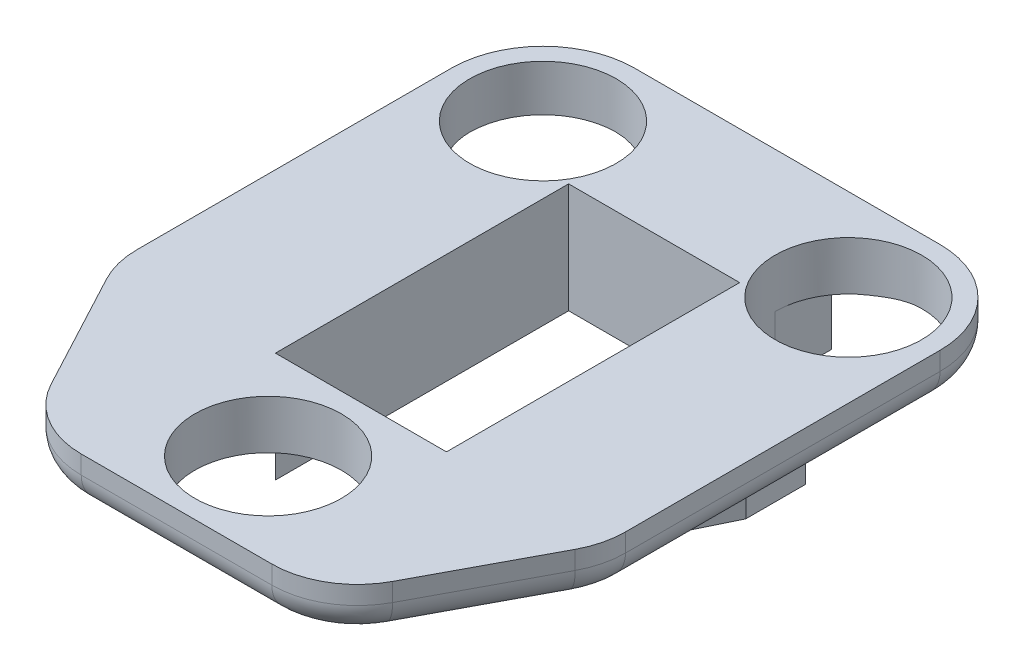
SolidWorks part; units mm, degrees
ref_plane "Front" through (0, 0, 0) normal (0, 0, 1) x (1, 0, 0)
ref_plane "Top" through (0, 0, 0) normal (0, 1, 0) x (1, 0, 0)
ref_plane "Right" through (0, 0, 0) normal (1, 0, 0) x (0, 0, -1)
sketch "Sketch2" plane through (0, 202.9635, 0) normal (0, -1, 0) x (1, 0, 0)
  line L6 (-139.7647, 258.9047) -> (-191.7647, 161.4047)
  line L7 (-200, 128.4635) -> (-200, -129.0365)
  line L8 (-125, -204.0365) -> (125, -204.0365)
  line L9 (200, -129.0365) -> (200, 128.4635)
  line L10 (191.7647, 161.4047) -> (139.7647, 258.9047)
  line L11 (78, 295.9635) -> (-78, 295.9635)
  line L12 (-139.7647, 258.9047) -> (-191.7647, 161.4047)
  line L13 (-200, 128.4635) -> (-200, -129.0365)
  line L14 (-125, -204.0365) -> (125, -204.0365)
  line L15 (200, -129.0365) -> (200, 128.4635)
  line L16 (191.7647, 161.4047) -> (139.7647, 258.9047)
  line L17 (78, 295.9635) -> (-78, 295.9635)
  arc A6 (-191.7647, 161.4047) -> (-200, 128.4635) centre (-130, 128.4635) ccw
  arc A7 (-200, -129.0365) -> (-125, -204.0365) centre (-125, -129.0365) ccw
  arc A8 (125, -204.0365) -> (200, -129.0365) centre (125, -129.0365) ccw
  arc A9 (200, 128.4635) -> (191.7647, 161.4047) centre (130, 128.4635) ccw
  arc A10 (139.7647, 258.9047) -> (78, 295.9635) centre (78, 225.9635) ccw
  arc A11 (-78, 295.9635) -> (-139.7647, 258.9047) centre (-78, 225.9635) ccw
  arc A12 (-191.7647, 161.4047) -> (-200, 128.4635) centre (-130, 128.4635) ccw
  arc A13 (-200, -129.0365) -> (-125, -204.0365) centre (-125, -129.0365) ccw
  arc A14 (125, -204.0365) -> (200, -129.0365) centre (125, -129.0365) ccw
  arc A15 (200, 128.4635) -> (191.7647, 161.4047) centre (130, 128.4635) ccw
  arc A16 (139.7647, 258.9047) -> (78, 295.9635) centre (78, 225.9635) ccw
  arc A17 (-78, 295.9635) -> (-139.7647, 258.9047) centre (-78, 225.9635) ccw
  dimension "D1" = 0
extrude "Boss-Extrude1" add sketch "Sketch2" along normal blind 40
fillet "Fillet1" radius 25 12 edges at (178.033, 162.9635, -182.0695) (0, 162.9635, -204.0365) (-178.033, 162.9635, -182.0695) (-200, 162.9635, -0.2865) (-197.91, 162.9635, 145.441) (-165.7647, 162.9635, 210.1547) (-114.0147, 162.9635, 285.988) (0, 162.9635, 295.9635) (114.0147, 162.9635, 285.988) (165.7647, 162.9635, 210.1547) (197.91, 162.9635, 145.441) (200, 162.9635, -0.2865)
sketch "Sketch3" plane through (0, 162.9635, 0) normal (0, -1, 0) x (1, 0, 0)
  line L0 (0, 145) -> (0, 0) construction
  line L1 (-70, 145) -> (70, 145)
  line L2 (-70, 145) -> (-70, -95)
  line L3 (-70, -95) -> (70, -95)
  line L4 (70, 145) -> (70, -95)
  line L5 (-125, -129) -> (125, -129) construction
  line L6 (0, 221) -> (0, -129) construction
  circle A3 centre (0, 221) radius 60
  circle A4 centre (125, -129) radius 60
  circle A5 centre (-125, -129) radius 60
  dimension "D7" = 120
  dimension "D1" = 145
  dimension "D2" = 70
  dimension "D3" = 240
  dimension "D4" = 129
  dimension "D5" = 250
  dimension "D6" = 350
extrude "Cut-Extrude1" cut sketch "Sketch3" against normal through all
sketch "Sketch4" plane through (0, 162.9635, 0) normal (0, -1, 0) x (1, 0, 0)
  line L0 (70, -95) -> (70, 145) construction
  line L2 (-150, -20) -> (-150, -69)
  line L3 (-150, -69) -> (-70, -69)
  line L4 (-70, 145) -> (-70, -69)
  line L6 (150, -20) -> (150, -69)
  line L7 (150, -69) -> (70, -69)
  line L8 (70, 145) -> (70, -69)
  line L9 (-70, 145) -> (-70, -95) construction
  line L11 (-70, -95) -> (70, -95) construction
  line L12 (-65, -95) -> (65, -95)
  line L13 (-65, -95) -> (-65, -175)
  line L14 (-65, -175) -> (65, -175)
  line L15 (65, -95) -> (65, -175)
  line L16 (0, -95) -> (0, 0) construction
  line L17 (70, -69) -> (70, -95)
  line L18 (70, -95) -> (65, -95)
  line L19 (-70, -69) -> (-70, -95)
  line L20 (-70, -95) -> (-65, -95)
  line L21 (-70, 145) -> (-150, -20)
  line L22 (70, 145) -> (150, -20)
  line L23 (-150, -20) -> (150, -20) construction
  arc A0 (-91.8889, -179.0365) -> (-175, -95.8338) centre (-125, -129) ccw construction
  arc A1 (-65, -129) -> (-125, -69) centre (-125, -129) ccw
  arc A2 (175, -95.8338) -> (91.8889, -179.0365) centre (125, -129) ccw construction
  arc A3 (125, -69) -> (65, -129) centre (125, -129) ccw
  dimension "D1" = 20
  dimension "D2" = 80
  dimension "D4" = 80
extrude "Boss-Extrude2" add sketch "Sketch4" along normal blind 50
